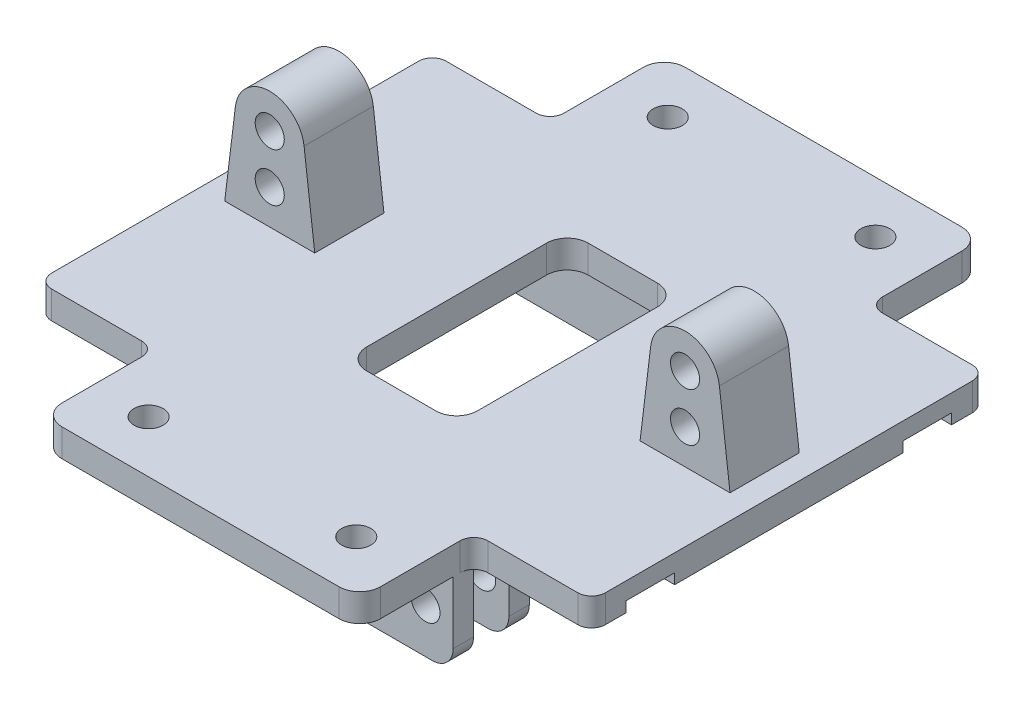
SolidWorks part; units mm, degrees
material "7075-T6，板材(SS)"
ref_plane "前视基准面" through (0, 0, 0) normal (0, 0, 1) x (1, 0, 0)
ref_plane "上视基准面" through (0, 0, 0) normal (0, 1, 0) x (1, 0, 0)
ref_plane "右视基准面" through (0, 0, 0) normal (1, 0, 0) x (0, 0, -1)
sketch "草图1" plane through (0, 0, 0) normal (0, 1, 0) x (1, 0, 0)
  line L1 (-20, -45) -> (20, -45)
  line L2 (-23, -42) -> (-23, 42)
  line L3 (-20, 45) -> (20, 45)
  line L4 (23, -42) -> (23, 42)
  line L5 (-23, -45) -> (23, 45) construction
  line L6 (-23, 45) -> (23, -45) construction
  arc A0 (20, -45) -> (23, -42) centre (20, -42) ccw
  arc A1 (-23, 42) -> (-20, 45) centre (-20, 42) cw
  arc A2 (-20, -45) -> (-23, -42) centre (-20, -42) cw
  arc A3 (20, 45) -> (23, 42) centre (20, 42) cw
  point P0 (0, 0)
  dimension "D3" = 3
  dimension "D1" = 90
  dimension "D2" = 46
extrude "凸台-拉伸1" add sketch "草图1" along normal blind 4
sketch "草图2" plane through (0, 4, 0) normal (0, 1, 0) x (1, 0, 0)
  line L1 (-40, -28.5) -> (40, -28.5)
  line L2 (-40, -28.5) -> (-40, 28.5)
  line L3 (-40, 28.5) -> (40, 28.5)
  line L4 (40, -28.5) -> (40, 28.5)
  line L5 (-40, -28.5) -> (40, 28.5) construction
  line L6 (-40, 28.5) -> (40, -28.5) construction
  point P0 (0, 0)
  dimension "D1" = 57
  dimension "D2" = 80
extrude "凸台-拉伸2" add sketch "草图2" against normal up to surface (4 mm away) up to face at (0, 0, 0)
fillet "圆角1" radius 2 8 edges at (-23, 2, -28.5) (-23, 2, 28.5) (23, 2, 28.5) (23, 2, -28.5) (40, 2, -28.5) (40, 2, 28.5) (-40, 2, 28.5) (-40, 2, -28.5)
sketch "草图3" plane through (0, 4, 0) normal (0, 1, 0) x (1, 0, 0)
  line L1 (-15, -37.5) -> (15, -37.5) construction
  line L2 (-15, -37.5) -> (-15, 37.5) construction
  line L3 (-15, 37.5) -> (15, 37.5) construction
  line L4 (15, -37.5) -> (15, 37.5) construction
  line L5 (-15, -37.5) -> (15, 37.5) construction
  line L6 (-15, 37.5) -> (15, -37.5) construction
  circle A0 centre (15, -37.5) radius 2.1
  circle A1 centre (-15, -37.5) radius 2.1
  circle A2 centre (-15, 37.5) radius 2.1
  circle A3 centre (15, 37.5) radius 2.1
  point P0 (0, 0)
  dimension "D3" = 4.2
  dimension "D1" = 75
  dimension "D2" = 30
extrude "切除-拉伸1" cut sketch "草图3" against normal through all
sketch "草图4" plane through (0, 0, 0) normal (0, 0, 1) x (1, 0, 0)
  line L0 (-34.9481, 16.7292) -> (-36.5, 4)
  line L1 (-38, 4) -> (-25, 4) construction
  line L2 (-36.5, 4) -> (-23.5, 4)
  line L3 (-30, 16) -> (-30, 28.0858) construction
  line L4 (-25.0519, 16.7292) -> (-23.5, 4)
  line L5 (0, 0) -> (0, 35.0043) construction
  line L6 (30, 16) -> (30, 28.0858) construction
  line L7 (25.0519, 16.7292) -> (23.5, 4)
  line L8 (36.5, 4) -> (23.5, 4)
  line L9 (34.9481, 16.7292) -> (36.5, 4)
  circle A0 centre (-30, 16) radius 2.1
  circle A1 centre (-30, 9) radius 2.1
  arc A3 (-25.0367, 16.6051) -> (-34.9633, 16.6051) centre (-30, 16) ccw
  arc A4 (25.0367, 16.6051) -> (34.9633, 16.6051) centre (30, 16) cw
  circle A5 centre (30, 9) radius 2.1
  circle A6 centre (30, 16) radius 2.1
  point P11 (-30, 4)
  point P28 (30, 4)
  dimension "D2" = 5
  dimension "D3" = 4.2
  dimension "D4" = 7
  dimension "D5" = 12
  dimension "D1" = 30
  dimension "D6" = 6.5
extrude "凸台-拉伸3" add sketch "草图4" along normal mid plane 10 contours L4 A3 L0 L2 A0 A1 | A4 L7 L8 L9 A5 A6
sketch "草图5" plane through (0, 0, 0) normal (0, -1, 0) x (1, 0, 0)
  line L0 (-20, 45) -> (20, 45) construction
  line L1 (-23, 31.5) -> (23, 31.5)
  line L2 (-23, 31.5) -> (-23, 20.5)
  line L3 (-23, 20.5) -> (23, 20.5)
  line L4 (23, 31.5) -> (23, 20.5)
  line L5 (-23, 31.5) -> (23, 20.5) construction
  line L6 (-23, 20.5) -> (23, 31.5) construction
  line L7 (23, 42) -> (23, 30.5) construction
  line L8 (-23, 30.5) -> (-23, 42) construction
  line L10 (-23, 23.45) -> (23, 23.45)
  line L11 (-23, 23.45) -> (-23, 28.55)
  line L12 (-23, 28.55) -> (23, 28.55)
  line L13 (23, 23.45) -> (23, 28.55)
  line L14 (-23, 23.45) -> (23, 28.55) construction
  line L15 (-23, 28.55) -> (23, 23.45) construction
  point P0 (0, 26)
  point P12 (0, 26)
  line M15 (23, 30.5) -> (23, 42)
  line M19 (-23, 42) -> (-23, 30.5)
  dimension "D1" = 19
  dimension "D2" = 11
  dimension "D3" = 5.1
extrude "凸台-拉伸4" add sketch "草图5" along normal blind 12 contours L2 L12 L4 L1 M15 M19 | L10 L2 L3 L4
mirror "镜向1" about plane through (0, 0, 0) normal (0, 0, 1) of "凸台-拉伸4"
sketch "草图6" plane through (0, 0, 31.5) normal (0, 0, 1) x (1, 0, 0)
  line L0 (-19, -5.5) -> (19, -5.5) construction
  line L1 (-23, 0) -> (23, 0) construction
  circle A0 centre (19, -5.5) radius 2.1
  circle A1 centre (-19, -5.5) radius 2.1
  point P4 (0, -5.5)
  dimension "D3" = 4.2
  dimension "D4" = 4.2
  dimension "D1" = 5.5
  dimension "D2" = 38
extrude "切除-拉伸2" cut sketch "草图6" against normal through all and the other way through all
fillet "圆角2" radius 3 8 edges at (23, -12, 30.025) (-23, -12, 30.025) (23, -12, 21.975) (-23, -12, 21.975) (-23, -12, -30.025) (23, -12, -30.025) (-23, -12, -21.975) (23, -12, -21.975)
sketch "草图7" plane through (-40, 0, 0) normal (-1, 0, 0) x (0, 0, 1)
  line L0 (-23.5, 0) -> (-23.5, 1.5)
  line L1 (26.5, 0) -> (-26.5, 0) construction
  line L2 (-23.5, 0) -> (-23.5, -64) construction
  line L3 (-23.5, 1.5) -> (-16.5, 1.5)
  line L4 (-16.5, 1.5) -> (-16.5, 0)
  line L5 (-16.5, 0) -> (-23.5, 0)
  dimension "D1" = 1.5
  dimension "D2" = 7
extrude "切除-拉伸3" cut sketch "草图7" against normal blind 15
mirror "镜向2" about plane through (0, 0, 0) normal (0, 0, 1) of "切除-拉伸3"
mirror "镜向3" about plane through (0, 0, 0) normal (1, 0, 0) of "镜向2", "切除-拉伸3"
sketch "草图8" plane through (0, 4, 0) normal (0, 1, 0) x (1, 0, 0)
  line L1 (-5, -16) -> (5, -16)
  line L2 (-8, -13) -> (-8, 13)
  line L3 (-5, 16) -> (5, 16)
  line L4 (8, -13) -> (8, 13)
  line L5 (-8, -16) -> (8, 16) construction
  line L6 (-8, 16) -> (8, -16) construction
  arc A0 (5, -16) -> (8, -13) centre (5, -13) ccw
  arc A1 (-8, 13) -> (-5, 16) centre (-5, 13) cw
  arc A2 (-5, -16) -> (-8, -13) centre (-5, -13) cw
  arc A3 (5, 16) -> (8, 13) centre (5, 13) cw
  point P0 (0, 0)
  dimension "D3" = 3
  dimension "D1" = 32
  dimension "D2" = 16
extrude "切除-拉伸4" cut sketch "草图8" against normal blind 10
